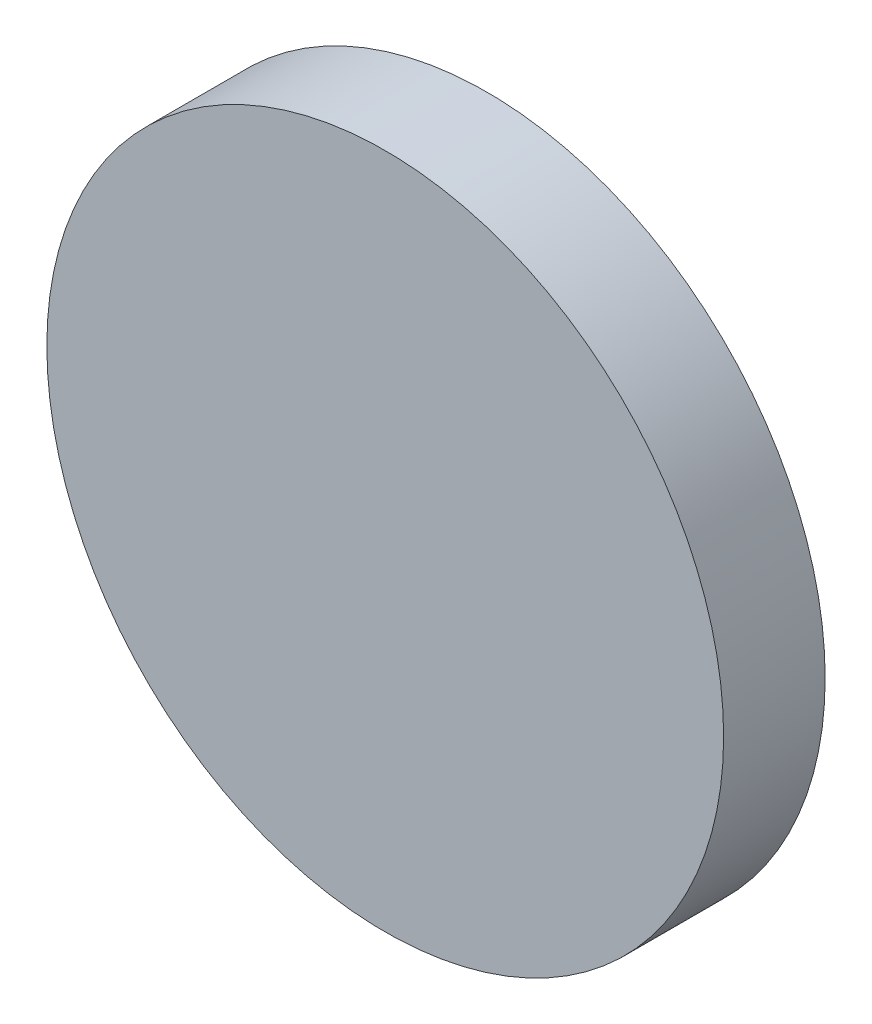
SolidWorks part; units mm, degrees
ref_plane "Plano frontal" through (0, 0, 0) normal (0, 0, 1) x (1, 0, 0)
ref_plane "Plano superior" through (0, 0, 0) normal (0, 1, 0) x (1, 0, 0)
ref_plane "Plano direito" through (0, 0, 0) normal (1, 0, 0) x (0, 0, -1)
sketch "Esboço1" plane through (0, 0, 0) normal (0, 0, 1) x (1, 0, 0)
  circle A0 centre (0, 0) radius 10
  dimension "D1" = 20
extrude "Ressalto-extrusão1" add sketch "Esboço1" along normal blind 3
